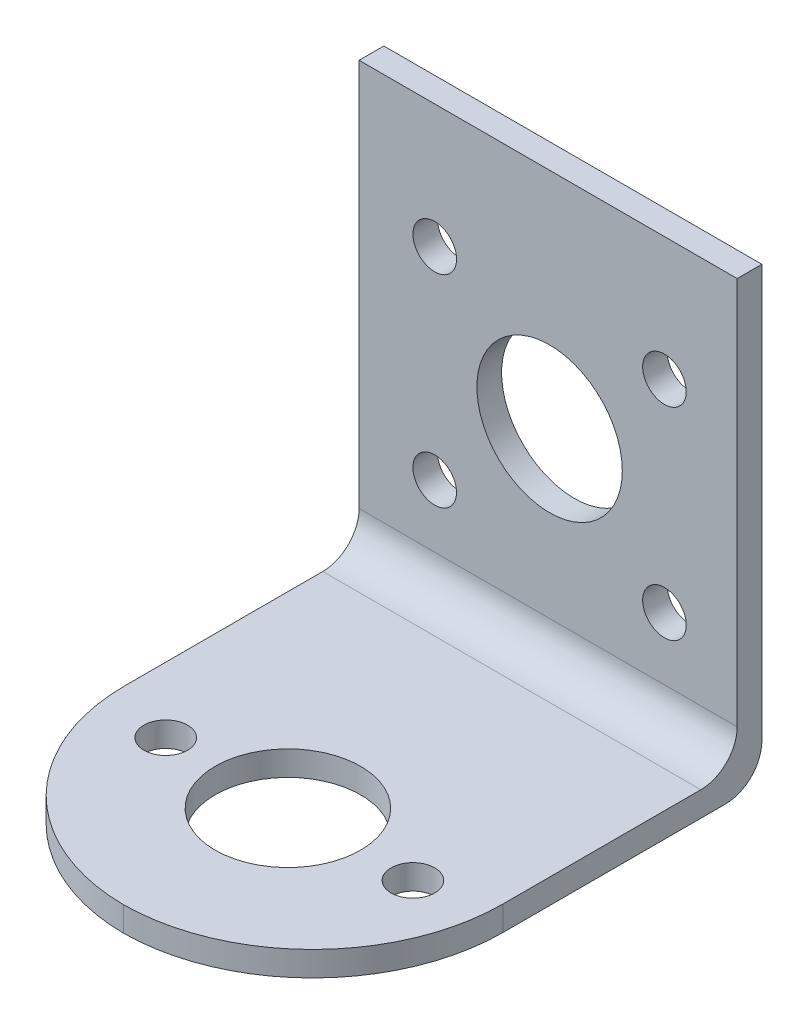
SolidWorks part; units mm, degrees
ref_plane "Front Plane" through (0, 0, 0) normal (0, 0, 1) x (1, 0, 0)
ref_plane "Top Plane" through (0, 0, 0) normal (0, 1, 0) x (1, 0, 0)
ref_plane "Right Plane" through (0, 0, 0) normal (1, 0, 0) x (0, 0, -1)
ref_plane "Plane1" through (0, -13.75, 0) normal (0, 1, 0) x (1, 0, 0)
sketch "Sketch1" plane through (0, -13.75, 0) normal (0, 1, 0) x (1, 0, 0)
  line L0 (13, -17.8) -> (13, 0)
  line L1 (13, 0) -> (-13, 0)
  line L2 (-13, 0) -> (-13, -17.8)
  arc A0 (-13, -17.8) -> (0, -30.8996) centre (0.1, -17.8) ccw
  arc A1 (0, -30.8996) -> (13, -17.8) centre (-0.1, -17.8) ccw
extrude "Boss-Extrude1" add sketch "Sketch1" against normal blind 1.7
sketch "Sketch2" plane through (0, -13.75, 0) normal (0, 1, 0) x (-1, 0, 0)
  line L0 (-13, 1.7) -> (13, 1.7)
  line L1 (13, 1.7) -> (13, 0)
  line L2 (13, 0) -> (-13, 0)
  line L3 (-13, 0) -> (-13, 1.7)
extrude "Boss-Extrude2" add sketch "Sketch2" along normal blind 29.2
hole_wizard "Ø10.0 (10) Diameter Hole1" positions "Sketch4" profile "Sketch3" hole size "Ø10.0" standard "ANSI Metric"
sketch "Sketch4" plane through (0, -13.75, 0) normal (0, 1, 0) x (1, 0, 0)
  point P0 (-0.1, -19.5)
sketch "Sketch3" plane through (-0.1, -13.75, 19.5) normal (1, 0, 0) x (0, 0, 1)
  line L0 (0, 0) -> (0, 1.7)
  line L1 (0, 1.7) -> (5, 1.7)
  line L2 (5, 1.7) -> (5, 0)
  line L5 (5, 0) -> (0, 0)
  line L11 (0, -6.35) -> (0, 107.95) construction
  dimension "Thru Hole Dia." = 10
  dimension "Thru Hole Depth" = 1.7
hole_wizard "Ø3.0 (3) Diameter Hole1" positions "Sketch6" profile "Sketch5" hole size "Ø3.0" standard "ANSI Metric" end condition through all
sketch "Sketch6" plane through (0, -13.75, 0) normal (0, 1, 0) x (1, 0, 0)
  line L0 (8.5, -19.5) -> (-8.5, -19.5)
  line L2 (0, -1.7) -> (0, -8.3107) construction
  point P0 (8.5, -19.5)
  point P1 (-8.5, -19.5)
  point P18 (0, -19.5)
  dimension "D1" = 17
sketch "Sketch5" plane through (8.5, -13.75, 19.5) normal (1, 0, 0) x (0, 0, 1)
  line L0 (0, 0) -> (0, 1.7)
  line L1 (0, 1.7) -> (1.5, 1.7)
  line L2 (1.5, 1.7) -> (1.5, 0)
  line L5 (1.5, 0) -> (0, 0)
  line L11 (0, -6.35) -> (0, 107.95) construction
  dimension "Thru Hole Dia." = 3
  dimension "Thru Hole Depth" = 1.7
hole_wizard "Ø10.0 (10) Diameter Hole2" positions "Sketch8" profile "Sketch7" hole size "Ø10.0" standard "ANSI Metric"
sketch "Sketch8" plane through (0, 0, 1.7) normal (0, 0, 1) x (1, 0, 0)
  point P0 (0.1, 0.05)
sketch "Sketch7" plane through (0.1, 0.05, 1.7) normal (1, 0, 0) x (0, -1, 0)
  line L0 (0, 0) -> (0, 1.7)
  line L1 (0, 1.7) -> (5, 1.7)
  line L2 (5, 1.7) -> (5, 0)
  line L5 (5, 0) -> (0, 0)
  line L11 (0, -6.35) -> (0, 107.95) construction
  dimension "Thru Hole Dia." = 10
  dimension "Thru Hole Depth" = 1.7
hole_wizard "Ø3.0 (3) Diameter Hole2" positions "Sketch10" profile "Sketch9" hole size "Ø3.0" standard "ANSI Metric"
sketch "Sketch10" plane through (0, 0, 1.7) normal (0, 0, 1) x (1, 0, 0)
  point P0 (-7.8, 6.95)
  point P1 (8, -6.95)
  point P2 (-7.8, -6.95)
  point P3 (8, 6.95)
sketch "Sketch9" plane through (-7.8, 6.95, 1.7) normal (1, 0, 0) x (0, -1, 0)
  line L0 (0, 0) -> (0, 1.7)
  line L1 (0, 1.7) -> (1.5, 1.7)
  line L2 (1.5, 1.7) -> (1.5, 0)
  line L5 (1.5, 0) -> (0, 0)
  line L11 (0, -6.35) -> (0, 107.95) construction
  dimension "Thru Hole Dia." = 3
  dimension "Thru Hole Depth" = 1.7
fillet "Fillet1" radius 2.5 2 edges at (0, -15.45, 0) (0, -13.75, 1.7)
